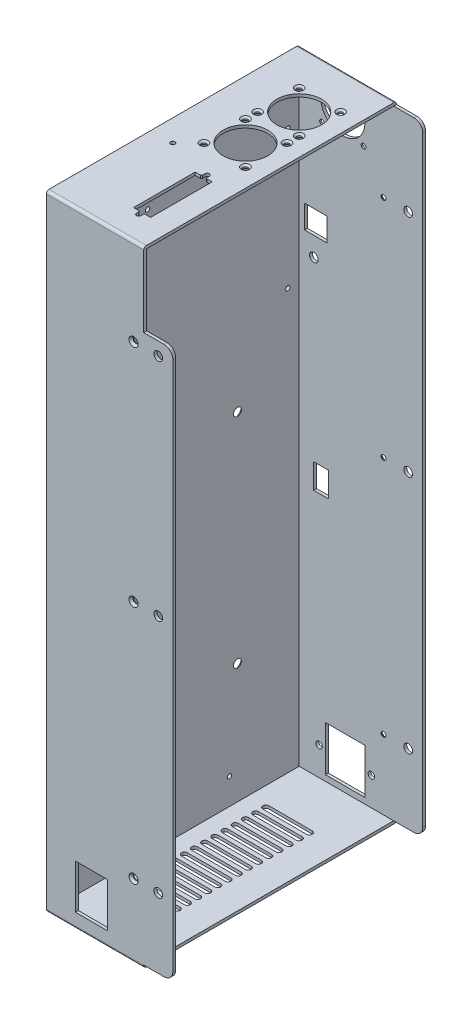
SolidWorks part; units mm, degrees
ref_plane "Front Plane" through (0, 0, 0) normal (0, 0, 1) x (1, 0, 0)
ref_plane "Top Plane" through (0, 0, 0) normal (0, 1, 0) x (1, 0, 0)
ref_plane "Right Plane" through (0, 0, 0) normal (1, 0, 0) x (0, 0, -1)
sketch "Sketch1" plane through (0, 0, 0) normal (1, 0, 0) x (0, 0, -1)
  line L0 (-87, 215) -> (87, -215) construction
  line L1 (-87, 215) -> (87, 215)
  line L2 (-87, 215) -> (-87, -215)
  line L3 (-87, -215) -> (87, -215)
  line L4 (87, 215) -> (87, -215)
  dimension "D1" = 430
  dimension "D2" = 174
extrude "Boss-Extrude1" add sketch "Sketch1" along normal blind 2
sketch "Sketch2" plane through (2, 0, 0) normal (1, 0, 0) x (0, 0, -1)
  line L8 (-85, 213) -> (-85, -213)
  line L9 (-85, -213) -> (85, -213)
  line L10 (85, -213) -> (85, 213)
  line L11 (85, 213) -> (-85, 213)
  line L12 (-85, 213) -> (-85, -213)
  line L13 (-85, -213) -> (85, -213)
  line L14 (85, -213) -> (85, 213)
  line L15 (85, 213) -> (-85, 213)
  line L16 (-87, 215) -> (-87, -215)
  line L17 (-87, -215) -> (87, -215)
  line L18 (87, -215) -> (87, 215)
  line L19 (87, 215) -> (-87, 215)
  line L20 (-87, 215) -> (-87, -215)
  line L21 (-87, -215) -> (87, -215)
  line L22 (87, -215) -> (87, 215)
  line L23 (87, 215) -> (-87, 215)
  dimension "D1" = 2
  dimension "D2" = 0
extrude "Boss-Extrude2" add sketch "Sketch2" along normal blind 65
sketch "Sketch3" plane through (67, 0, 0) normal (1, 0, 0) x (0, 0, -1)
  line L0 (-85, -213) -> (85, -213) construction
  line L1 (-85, 164) -> (-87, 164)
  line L2 (-85, 164) -> (-85, -213)
  line L3 (-85, -213) -> (-87, -213)
  line L4 (-87, 164) -> (-87, -213)
  line L5 (85, 213) -> (87, 213)
  line L6 (85, 213) -> (85, -213)
  line L7 (85, -213) -> (87, -213)
  line L8 (87, 213) -> (87, -213)
  line L9 (-87, 215) -> (-87, -215) construction
  line L10 (87, -215) -> (87, 215) construction
  line L11 (-85, 213) -> (-85, -213) construction
  line L12 (87, 215) -> (-87, 215) construction
  dimension "D1" = 51
extrude "Boss-Extrude3" add sketch "Sketch3" along normal blind 20
fillet "Fillet1" radius 1.8 4 edges at (33.5, -215, -87) (33.5, -215, 87) (33.5, 215, -87) (33.5, 215, 87)
sketch "Sketch4" plane through (0, 0, 87) normal (0, 0, 1) x (1, 0, 0)
  line L0 (67, -215) -> (0, -215) construction
  line L1 (20, -174.5) -> (42.15, -174.5)
  line L2 (20, -174.5) -> (20, -205)
  line L3 (20, -205) -> (42.15, -205)
  line L4 (42.15, -174.5) -> (42.15, -205)
  line L5 (0, 213.2) -> (0, -213.2) construction
  dimension "D1" = 30.5
  dimension "D2" = 22.15
  dimension "D3" = 10
  dimension "D4" = 20
extrude "Cut-Extrude1" cut sketch "Sketch4" against normal blind 5
sketch "Sketch5" plane through (0, 0, -87) normal (0, 0, -1) x (-1, 0, 0)
  line L0 (-47.3, -177.9) -> (-20, -209) construction
  line L1 (-47.3, -177.9) -> (-20, -177.9)
  line L2 (-47.3, -177.9) -> (-47.3, -209)
  line L3 (-47.3, -209) -> (-20, -209)
  line L4 (-20, -177.9) -> (-20, -209)
  line L5 (-51.65, -193.45) -> (-33.65, -193.45) construction
  line L6 (-33.65, -193.45) -> (-15.65, -193.45) construction
  line L7 (0, -215) -> (-67, -215) construction
  line L8 (0, -213.2) -> (0, 213.2) construction
  line L9 (-7.778, 110.48) -> (-7.778, 122.48) construction
  line L10 (-21.081, 124.48) -> (-5.778, 124.48)
  line L11 (-21.081, 124.48) -> (-21.081, 108.48)
  line L12 (-21.081, 108.48) -> (-5.778, 108.48)
  line L13 (-5.778, 124.48) -> (-5.778, 108.48)
  line L14 (-19.081, 110.48) -> (-7.778, 110.48) construction
  line L15 (-19.081, 110.48) -> (-19.081, 122.48) construction
  line L16 (-19.081, 122.48) -> (-7.778, 122.48) construction
  line L17 (-21, -42.5) -> (-13, -42.5) construction
  line L18 (-22, -26.5) -> (-12, -26.5)
  line L19 (-22, -26.5) -> (-22, -43.5)
  line L20 (-22, -43.5) -> (-12, -43.5)
  line L21 (-12, -26.5) -> (-12, -43.5)
  line L22 (-13, -42.5) -> (-13, -27.5) construction
  line L23 (-13, -27.5) -> (-21, -27.5) construction
  line L24 (-21, -27.5) -> (-21, -42.5) construction
  line L25 (-46.2875, 207.2875) -> (-17.7125, 178.7125) construction
  line L26 (-67, 215) -> (0, 215) construction
  line L27 (-87, -213) -> (-87, 213) construction
  circle A0 centre (-51.65, -193.45) radius 2.25
  circle A1 centre (-15.65, -193.45) radius 2.25
  circle A2 centre (-12.096, 95.3) radius 3
  circle A3 centre (-32, 193) radius 15.187
  circle A4 centre (-46.2875, 207.2875) radius 1
  circle A5 centre (-17.7125, 207.2875) radius 1
  circle A6 centre (-46.2875, 178.7125) radius 1
  circle A7 centre (-17.7125, 178.7125) radius 1
  dimension "D4" = 4.5
  dimension "D7" = 6
  dimension "D16" = 2
  dimension "D19" = 30.374
  dimension "D20" = 28.575
  dimension "D1" = 27.3
  dimension "D2" = 31.1
  dimension "D3" = 36
  dimension "D5" = 6
  dimension "D6" = 20
  dimension "D8" = 2
  dimension "D9" = 2
  dimension "D10" = 2
  dimension "D11" = 2
  dimension "D12" = 1
  dimension "D13" = 1
  dimension "D14" = 1
  dimension "D15" = 1
  dimension "D17" = 22
  dimension "D18" = 55
  dimension "D21" = 28.575
extrude "Cut-Extrude2" cut sketch "Sketch5" against normal blind 5
sketch "Sketch6" plane through (0, 215, 0) normal (0, 1, 0) x (1, 0, 0)
  line L0 (0, 85.2) -> (0, -85.2) construction
  line L1 (0, 87) -> (67, 87) construction
  line L2 (25.7125, 61.2875) -> (54.2875, 32.7125) construction
  line L3 (54.2875, 24.2875) -> (25.7125, -4.2875) construction
  line L4 (40, -24.6) -> (51.73, -67) construction
  line L5 (40, -24.6) -> (43.528, -24.6)
  line L6 (40, -24.6) -> (40, -67)
  line L7 (40, -67) -> (43.528, -67)
  line L8 (51.73, -24.6) -> (51.73, -67)
  line L9 (45.865, -22.3) -> (45.865, -45.8) construction
  line L10 (45.865, -45.8) -> (45.865, -69.3) construction
  line L11 (67, -87) -> (0, -87) construction
  line L12 (44.341, -22.3) -> (44.341, -23.787)
  line L13 (47.389, -69.3) -> (47.389, -67.813)
  line L14 (44.341, -67.813) -> (44.341, -69.3)
  line L15 (48.202, -24.6) -> (51.73, -24.6)
  line L16 (47.389, -23.787) -> (47.389, -22.3)
  line L17 (48.202, -67) -> (51.73, -67)
  circle A0 centre (40, 47) radius 15.367
  circle A1 centre (40, 10) radius 15.367
  circle A2 centre (25.7125, 61.2875) radius 1
  circle A3 centre (25.7125, 32.7125) radius 1
  circle A4 centre (25.7125, 24.2875) radius 1
  circle A5 centre (25.7125, -4.2875) radius 1
  circle A6 centre (54.2875, -4.2875) radius 1
  circle A7 centre (54.2875, 24.2875) radius 1
  circle A8 centre (54.2875, 32.7125) radius 1
  circle A9 centre (54.2875, 61.2875) radius 1
  arc A10 (47.389, -22.3) -> (44.341, -22.3) centre (45.865, -22.3) ccw
  arc A11 (44.341, -69.3) -> (47.389, -69.3) centre (45.865, -69.3) ccw
  arc A12 (44.341, -67.813) -> (43.528, -67) centre (43.528, -67.813) ccw
  arc A13 (47.389, -67.813) -> (48.202, -67) centre (48.202, -67.813) cw
  arc A14 (48.202, -24.6) -> (47.389, -23.787) centre (48.202, -23.787) cw
  arc A15 (44.341, -23.787) -> (43.528, -24.6) centre (43.528, -23.787) cw
  circle A16 centre (15, -15) radius 1.5
  point P45 (47.389, -67)
  point P48 (47.389, -24.6)
  dimension "D4" = 30.734
  dimension "D6" = 2
  dimension "D13" = 3.048
  dimension "D15" = 0.813
  dimension "D18" = 3
  dimension "D1" = 37
  dimension "D2" = 40
  dimension "D3" = 40
  dimension "D5" = 28.575
  dimension "D7" = 28.575
  dimension "D8" = 28.575
  dimension "D9" = 40
  dimension "D10" = 42.4
  dimension "D11" = 47
  dimension "D12" = 11.73
  dimension "D14" = 20
  dimension "D16" = 25
  dimension "D17" = 25
extrude "Cut-Extrude3" cut sketch "Sketch6" against normal blind 5
hole_wizard "CSK for #4 Flat Head Machine Screw (100)1" positions "Sketch8" profile "Sketch7" countersink size "#4" standard "Ansi Inch"
sketch "Sketch8" plane through (0, 215, 0) normal (0, 1, 0) x (-1, 0, 0)
  point P0 (-25.7125, 4.2875)
  point P1 (-25.7125, -61.2875)
  point P4 (-54.2875, -61.2875)
  point P7 (-54.2875, -32.7125)
  point P10 (-25.7125, -32.7125)
  point P13 (-25.7125, -24.2875)
  point P16 (-54.2875, -24.2875)
  point P19 (-54.2875, 4.2875)
sketch "Sketch7" plane through (25.7125, 215, 4.2875) normal (1, 0, 0) x (0, 0, 1)
  line L0 (0, 0) -> (0, 10.9806)
  line L1 (0, 10.9806) -> (1.6319, 10)
  line L2 (1.6319, 10) -> (1.6319, 1.0284)
  line L3 (1.6319, 1.0284) -> (2.8575, 0)
  line L5 (2.8575, 0) -> (0, 0)
  line L6 (-1.6319, 1.0284) -> (-2.8575, 0) construction
  line L10 (0, 10.9806) -> (-1.6319, 10) construction
  line L11 (0, -6.35) -> (0, 107.95) construction
  dimension "Hole Dia." = 3.2639
  dimension "Hole Depth" = 10
  dimension "Near C'Sink Dia." = 5.715
  dimension "Near C'Sink Angle" = 100
  dimension "Drill Angle" = 118
hole_wizard "CSK for #4 Flat Head Machine Screw (100)2" positions "Sketch10" profile "Sketch9" countersink size "#4" standard "Ansi Inch"
sketch "Sketch10" plane through (0, 0, -87) normal (0, 0, -1) x (-1, 0, 0)
  point P0 (-46.2875, 207.2875)
  point P1 (-17.7125, 207.2875)
  point P4 (-17.7125, 178.7125)
  point P7 (-46.2875, 178.7125)
sketch "Sketch9" plane through (46.2875, 207.2875, -87) normal (1, 0, 0) x (0, 1, 0)
  line L0 (0, 0) -> (0, 10.9806)
  line L1 (0, 10.9806) -> (1.6319, 10)
  line L2 (1.6319, 10) -> (1.6319, 1.0284)
  line L3 (1.6319, 1.0284) -> (2.8575, 0)
  line L5 (2.8575, 0) -> (0, 0)
  line L6 (-1.6319, 1.0284) -> (-2.8575, 0) construction
  line L10 (0, 10.9806) -> (-1.6319, 10) construction
  line L11 (0, -6.35) -> (0, 107.95) construction
  dimension "Hole Dia." = 3.2639
  dimension "Hole Depth" = 10
  dimension "Near C'Sink Dia." = 5.715
  dimension "Near C'Sink Angle" = 100
  dimension "Drill Angle" = 118
sketch "Sketch11" plane through (2, 0, 0) normal (1, 0, 0) x (0, 0, -1)
  line L0 (-85.2, -215) -> (85.2, -215) construction
  line L1 (87, -213) -> (87, 213) construction
  circle A0 centre (-19.33, 171.06) radius 1.5
  circle A1 centre (77.19, 171.06) radius 1.5
  circle A2 centre (-19.33, 75.81) radius 1.5
  circle A3 centre (77.19, 75.81) radius 1.5
  circle A4 centre (-7.5, 19.5) radius 1.5
  circle A5 centre (42.5, 19.5) radius 1.5
  circle A6 centre (42.5, -130.5) radius 1.5
  circle A7 centre (-7.5, -130.5) radius 1.5
  circle A8 centre (37, -195) radius 1.5
  dimension "D1" = 3
  dimension "D2" = 3
  dimension "D4" = 3
  dimension "D3" = 20
  dimension "D5" = 50
extrude "Cut-Extrude4" cut sketch "Sketch11" against normal blind 5
hole_wizard "CSK for M4 Flat Head Machine Screw1" positions "Sketch13" profile "Sketch12" countersink size "M4" standard "Ansi Metric"
sketch "Sketch13" plane through (0, 0, 0) normal (-1, 0, 0) x (0, 0, 1)
  point P0 (-42.5, 19.5)
  point P1 (7.5, 19.5)
  point P4 (7.5, -130.5)
  point P7 (-42.5, -130.5)
sketch "Sketch12" plane through (0, 19.5, -42.5) normal (0, 1, 0) x (0, 0, 1)
  line L0 (0, 0) -> (0, 11.3519)
  line L1 (0, 11.3519) -> (2.25, 10)
  line L2 (2.25, 10) -> (2.25, 2.45)
  line L3 (2.25, 2.45) -> (4.7, 0)
  line L5 (4.7, 0) -> (0, 0)
  line L6 (-2.25, 2.45) -> (-4.7, 0) construction
  line L10 (0, 11.3519) -> (-2.25, 10) construction
  line L11 (0, -6.35) -> (0, 107.95) construction
  dimension "Hole Dia." = 4.5
  dimension "Hole Depth" = 10
  dimension "Near C'Sink Dia." = 9.4
  dimension "Near C'Sink Angle" = 90
  dimension "Drill Angle" = 118
sketch "Sketch14" plane through (0, 0, 87) normal (0, 0, 1) x (1, 0, 0)
  line L0 (87, 164) -> (87, -213) construction
  line L1 (0, 0) -> (77, 0) construction
  circle A0 centre (60, 155) radius 1.5
  circle A1 centre (60, 0) radius 1.5
  circle A2 centre (60, -165) radius 1.5
  circle A3 centre (77, 155) radius 3
  circle A4 centre (77, 0) radius 3
  circle A5 centre (77, -165) radius 3
  dimension "D2" = 3
  dimension "D3" = 6
  dimension "D5" = 165
  dimension "D1" = 10
  dimension "D4" = 155
extrude "Cut-Extrude5" cut sketch "Sketch14" against normal through all
hole_wizard "CSK for M3 Flat Head Machine Screw1" positions "Sketch16" profile "Sketch15" countersink size "M3" standard "Ansi Metric"
sketch "Sketch16" plane through (0, 0, -87) normal (0, 0, -1) x (-1, 0, 0)
  point P0 (-60, 155)
  point P1 (-60, 0)
  point P4 (-60, -165)
sketch "Sketch15" plane through (60, 155, -87) normal (1, 0, 0) x (0, 1, 0)
  line L0 (0, 0) -> (0, 11.0215)
  line L1 (0, 11.0215) -> (1.7, 10)
  line L2 (1.7, 10) -> (1.7, 1.45)
  line L3 (1.7, 1.45) -> (3.15, 0)
  line L5 (3.15, 0) -> (0, 0)
  line L6 (-1.7, 1.45) -> (-3.15, 0) construction
  line L10 (0, 11.0215) -> (-1.7, 10) construction
  line L11 (0, -6.35) -> (0, 107.95) construction
  dimension "Hole Dia." = 3.4
  dimension "Hole Depth" = 10
  dimension "Near C'Sink Dia." = 6.3
  dimension "Near C'Sink Angle" = 90
  dimension "Drill Angle" = 118
hole_wizard "CSK for M3 Flat Head Machine Screw2" positions "Sketch18" profile "Sketch19" countersink size "M3" standard "Ansi Metric" end condition through all
sketch "Sketch18" plane through (0, 0, 87) normal (0, 0, 1) x (1, 0, 0)
  point P0 (60, 155)
  point P5 (60, 0)
  point P8 (60, -165)
sketch "Sketch19" plane through (60, 155, 87) normal (1, 0, 0) x (0, -1, 0)
  line L0 (0, 0) -> (0, 174)
  line L1 (0, 174) -> (1.7, 174)
  line L2 (1.7, 174) -> (1.7, 1.45)
  line L3 (1.7, 1.45) -> (3.15, 0)
  line L5 (3.15, 0) -> (0, 0)
  line L6 (-1.7, 1.45) -> (-3.15, 0) construction
  line L11 (0, -6.35) -> (0, 107.95) construction
  dimension "Thru Hole Dia." = 3.4
  dimension "Thru Hole Depth" = 174
  dimension "Near C'Sink Dia." = 6.3
  dimension "Near C'Sink Angle" = 90
sketch "Sketch20" plane through (0, -215, 0) normal (0, -1, 0) x (1, 0, 0)
  line L0 (15, 35) -> (45, 35) construction
  line L1 (15, 37) -> (45, 37)
  line L2 (15, 33) -> (45, 33)
  line L3 (15, 28) -> (45, 28) construction
  line L4 (15, 30) -> (45, 30)
  line L5 (15, 26) -> (45, 26)
  line L6 (15, 21) -> (45, 21) construction
  line L7 (15, 23) -> (45, 23)
  line L8 (15, 19) -> (45, 19)
  line L9 (15, 14) -> (45, 14) construction
  line L10 (15, 16) -> (45, 16)
  line L11 (15, 12) -> (45, 12)
  line L12 (15, 7) -> (45, 7) construction
  line L13 (15, 9) -> (45, 9)
  line L14 (15, 5) -> (45, 5)
  line L15 (15, 0) -> (45, 0) construction
  line L16 (15, 2) -> (45, 2)
  line L17 (15, -2) -> (45, -2)
  line L18 (30, 35) -> (30, 28) construction
  line L19 (30, 28) -> (30, 21) construction
  line L20 (30, 21) -> (30, 14) construction
  line L21 (30, 14) -> (30, 7) construction
  line L22 (30, 7) -> (30, 0) construction
  line L24 (0, 85.2) -> (0, -85.2) construction
  line L25 (15, -7) -> (45, -7) construction
  line L26 (15, -5) -> (45, -5)
  line L27 (15, -9) -> (45, -9)
  line L28 (15, -14) -> (45, -14) construction
  line L29 (15, -12) -> (45, -12)
  line L30 (15, -16) -> (45, -16)
  line L31 (15, -21) -> (45, -21) construction
  line L32 (15, -19) -> (45, -19)
  line L33 (15, -23) -> (45, -23)
  line L34 (15, -28) -> (45, -28) construction
  line L35 (15, -26) -> (45, -26)
  line L36 (15, -30) -> (45, -30)
  line L37 (15, -35) -> (45, -35) construction
  line L38 (15, -33) -> (45, -33)
  line L39 (15, -37) -> (45, -37)
  line L40 (30, 0) -> (30, -7) construction
  line L41 (30, -7) -> (30, -14) construction
  line L42 (30, -14) -> (30, -21) construction
  line L43 (30, -21) -> (30, -28) construction
  line L44 (30, -28) -> (30, -35) construction
  line L45 (15, 42) -> (45, 42) construction
  line L46 (15, 44) -> (45, 44)
  line L47 (15, 40) -> (45, 40)
  line L48 (15, 49) -> (45, 49) construction
  line L49 (15, 51) -> (45, 51)
  line L50 (15, 47) -> (45, 47)
  line L51 (15, -42) -> (45, -42) construction
  line L52 (15, -40) -> (45, -40)
  line L53 (15, -44) -> (45, -44)
  line L54 (15, -49) -> (45, -49) construction
  line L55 (15, -47) -> (45, -47)
  line L56 (15, -51) -> (45, -51)
  line L57 (30, 35) -> (30, 42) construction
  line L58 (30, 42) -> (30, 49) construction
  line L59 (30, -35) -> (30, -42) construction
  line L60 (30, -42) -> (30, -49) construction
  arc A0 (15, 37) -> (15, 33) centre (15, 35) ccw
  arc A1 (45, 33) -> (45, 37) centre (45, 35) ccw
  arc A2 (15, 30) -> (15, 26) centre (15, 28) ccw
  arc A3 (45, 26) -> (45, 30) centre (45, 28) ccw
  arc A4 (15, 23) -> (15, 19) centre (15, 21) ccw
  arc A5 (45, 19) -> (45, 23) centre (45, 21) ccw
  arc A6 (15, 16) -> (15, 12) centre (15, 14) ccw
  arc A7 (45, 12) -> (45, 16) centre (45, 14) ccw
  arc A8 (15, 9) -> (15, 5) centre (15, 7) ccw
  arc A9 (45, 5) -> (45, 9) centre (45, 7) ccw
  arc A10 (15, 2) -> (15, -2) centre (15, 0) ccw
  arc A11 (45, -2) -> (45, 2) centre (45, 0) ccw
  arc A12 (15, -5) -> (15, -9) centre (15, -7) ccw
  arc A13 (45, -9) -> (45, -5) centre (45, -7) ccw
  arc A14 (15, -12) -> (15, -16) centre (15, -14) ccw
  arc A15 (45, -16) -> (45, -12) centre (45, -14) ccw
  arc A16 (15, -19) -> (15, -23) centre (15, -21) ccw
  arc A17 (45, -23) -> (45, -19) centre (45, -21) ccw
  arc A18 (15, -26) -> (15, -30) centre (15, -28) ccw
  arc A19 (45, -30) -> (45, -26) centre (45, -28) ccw
  arc A20 (15, -33) -> (15, -37) centre (15, -35) ccw
  arc A21 (45, -37) -> (45, -33) centre (45, -35) ccw
  arc A22 (15, 44) -> (15, 40) centre (15, 42) ccw
  arc A23 (45, 40) -> (45, 44) centre (45, 42) ccw
  arc A24 (15, 51) -> (15, 47) centre (15, 49) ccw
  arc A25 (45, 47) -> (45, 51) centre (45, 49) ccw
  arc A26 (15, -40) -> (15, -44) centre (15, -42) ccw
  arc A27 (45, -44) -> (45, -40) centre (45, -42) ccw
  arc A28 (15, -47) -> (15, -51) centre (15, -49) ccw
  arc A29 (45, -51) -> (45, -47) centre (45, -49) ccw
  point P2 (30, 35)
  point P7 (30, 28)
  point P14 (30, 21)
  point P21 (30, 14)
  point P28 (30, 7)
  point P35 (30, 0)
  point P52 (30, -7)
  point P58 (30, -14)
  point P65 (30, -21)
  point P72 (30, -28)
  point P79 (30, -35)
  point P93 (30, 42)
  point P100 (30, 49)
  point P105 (30, -42)
  point P112 (30, -49)
  dimension "D1" = 2
  dimension "D2" = 7
  dimension "D4" = 15
  dimension "D5" = 30
extrude "Cut-Extrude6" cut sketch "Sketch20" against normal blind 10
fillet "Fillet2" radius 6 4 edges at (87, 164, 86) (87, 213, -86) (87, -213, -86) (87, -213, 86)
